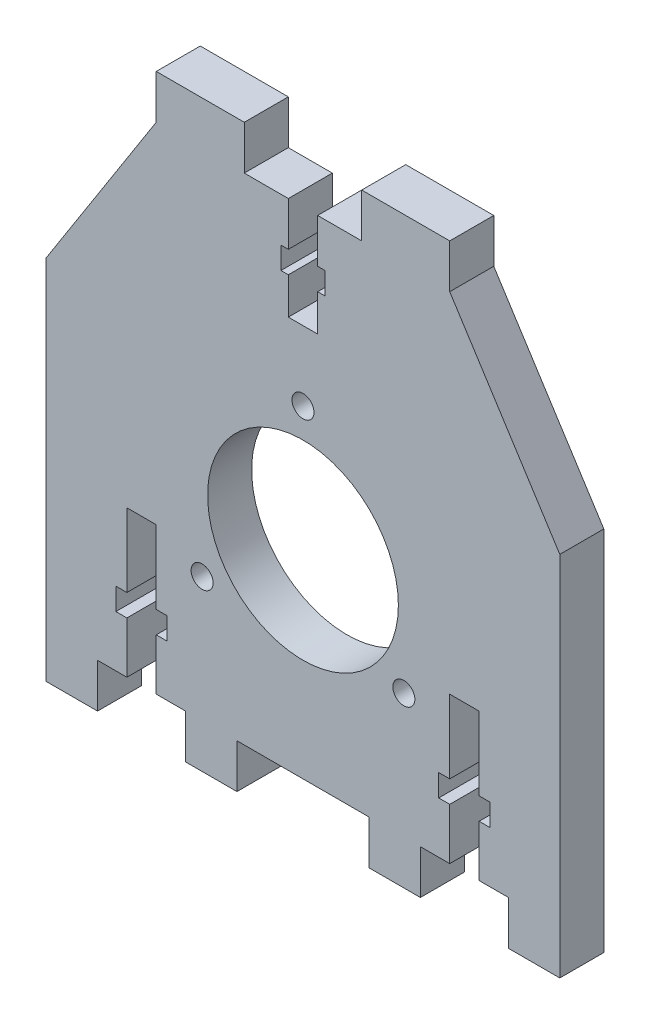
SolidWorks part; units mm, degrees
material "Balsa"
ref_plane "Plan de face" through (0, 0, 0) normal (0, 0, 1) x (1, 0, 0)
ref_plane "Plan de dessus" through (0, 0, 0) normal (0, 1, 0) x (1, 0, 0)
ref_plane "Plan de droite" through (0, 0, 0) normal (1, 0, 0) x (0, 0, -1)
sketch "Esquisse1" plane through (0, 0, 0) normal (0, 0, 1) x (1, 0, 0)
  line L0 (55, 13) -> (53.5, 13)
  line L1 (7, 6) -> (11, 6)
  line L2 (15, 6) -> (19, 6)
  line L3 (15, 73.5) -> (55, 73.5)
  line L4 (11, 16) -> (11, 26)
  line L5 (15, 73.5) -> (0, 50)
  line L6 (35, 73.5) -> (35, 6) construction
  line L7 (11, 6) -> (11, 13)
  line L8 (0, 50) -> (0, 0)
  line L9 (0, 0) -> (7, 0)
  line L10 (7, 6) -> (7, 0)
  line L11 (11, 26) -> (15, 26)
  line L12 (19, 6) -> (19, 0)
  line L13 (19, 0) -> (26, 0)
  line L14 (26, 6) -> (26, 0)
  line L15 (26, 6) -> (44, 6)
  line L16 (55, 16) -> (55, 26)
  line L17 (55, 16) -> (53.5, 16)
  line L18 (53.5, 16) -> (53.5, 13)
  line L19 (60.5, 13) -> (59, 13)
  line L20 (60.5, 16) -> (60.5, 13)
  line L21 (60.5, 16) -> (59, 16)
  line L22 (55, 6) -> (55, 13)
  line L23 (15, 6) -> (15, 13)
  line L24 (44, 6) -> (44, 0)
  line L25 (51, 0) -> (44, 0)
  line L26 (51, 6) -> (51, 0)
  line L27 (59, 26) -> (55, 26)
  line L28 (9.5, 16) -> (11, 16)
  line L29 (9.5, 16) -> (9.5, 13)
  line L30 (9.5, 13) -> (11, 13)
  line L31 (16.5, 16) -> (16.5, 13)
  line L32 (15, 16) -> (16.5, 16)
  line L33 (15, 16) -> (15, 26)
  line L34 (15, 13) -> (16.5, 13)
  line L35 (63, 6) -> (63, 0)
  line L36 (70, 0) -> (63, 0)
  line L37 (70, 50) -> (70, 0)
  line L38 (59, 6) -> (59, 13)
  line L39 (55, 73.5) -> (70, 50)
  line L40 (59, 16) -> (59, 26)
  line L41 (55, 6) -> (51, 6)
  line L42 (63, 6) -> (59, 6)
  circle A0 centre (35, 33) radius 13
  dimension "D6" = 26
  dimension "D3" = 7
  dimension "D4" = 7
  dimension "D5" = 12
  dimension "D7" = 35
  dimension "D8" = 27
  dimension "D9" = 6
  dimension "D10" = 67.5
  dimension "D11" = 20
  dimension "D12" = 50
  dimension "D16" = 4
  dimension "D19" = 4
  dimension "D20" = 10
  dimension "D21" = 26
  dimension "D22" = 3
  dimension "D23" = 7
  dimension "D24" = 1.5
extrude "Boss.-Extru.1" add sketch "Esquisse1" along normal blind 6
sketch "Esquisse2" plane through (0, 73.5, 0) normal (0, 1, 0) x (1, 0, 0)
  line L0 (55, 0) -> (15, 0) construction
  line L1 (15, 0) -> (27, 0)
  line L2 (15, 0) -> (15, -6)
  line L3 (15, -6) -> (27, -6)
  line L4 (27, 0) -> (27, -6)
  line L5 (55, -6) -> (15, -6) construction
  line L6 (15, -6) -> (15, 0) construction
  line L7 (55, -6) -> (15, -6) construction
  line L8 (55, 0) -> (43, 0)
  line L9 (55, 0) -> (55, -6)
  line L10 (55, -6) -> (43, -6)
  line L11 (43, 0) -> (43, -6)
  dimension "D1" = 12
  dimension "D2" = 12
extrude "Boss.-Extru.2" add sketch "Esquisse2" along normal blind 6
sketch "Esquisse3" plane through (0, 0, 6) normal (0, 0, 1) x (1, 0, 0)
  line L0 (21.2523, 23) -> (48.7477, 23) construction
  circle A0 centre (35, 33) radius 17 construction
  circle A2 centre (21.2523, 23) radius 1.5
  circle A3 centre (48.7477, 23) radius 1.5
  circle A4 centre (35, 50) radius 1.5
  circle A7 centre (35, 33) radius 13 construction
  dimension "D1" = 34
  dimension "D2" = 3
  dimension "D3" = 3
  dimension "D4" = 10
extrude "Enlèv. mat.-Extru.1" cut sketch "Esquisse3" against normal blind 10
sketch "Esquisse4" plane through (0, 0, 6) normal (0, 0, 1) x (1, 0, 0)
  line L0 (43, 73.5) -> (27, 73.5) construction
  line L1 (33, 73.5) -> (37, 73.5)
  line L2 (33, 73.5) -> (33, 67.5)
  line L3 (33, 59.5) -> (37, 59.5)
  line L4 (37, 73.5) -> (37, 67.5)
  line L5 (35, 59.5) -> (35, 73.5) construction
  line L6 (37, 67.5) -> (38, 67.5)
  line L7 (32, 67.5) -> (33, 67.5)
  line L8 (32, 67.5) -> (32, 64.5)
  line L9 (32, 64.5) -> (33, 64.5)
  line L10 (38, 67.5) -> (38, 64.5)
  line L11 (33, 64.5) -> (33, 59.5)
  line L12 (37, 64.5) -> (38, 64.5)
  line L13 (37, 64.5) -> (37, 59.5)
  point P12 (35, 67.5)
  dimension "D1" = 2
  dimension "D2" = 14
  dimension "D3" = 3
  dimension "D4" = 6
  dimension "D5" = 6
extrude "Enlèv. mat.-Extru.2" cut sketch "Esquisse4" against normal blind 10
